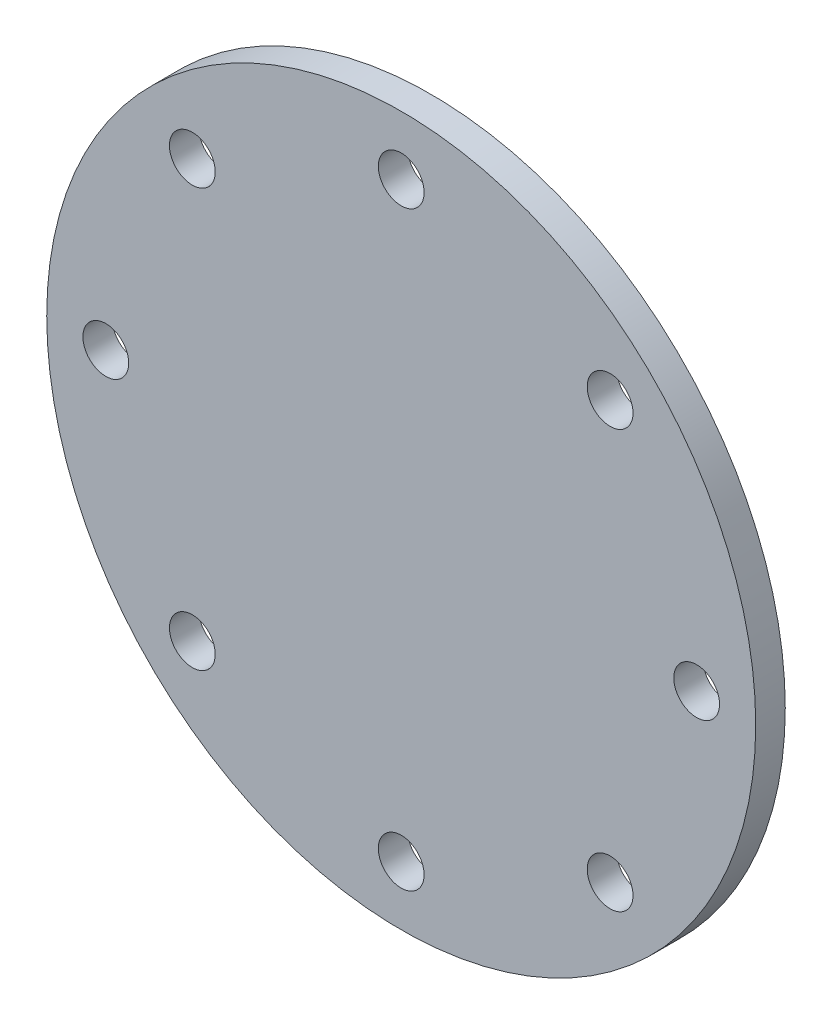
SolidWorks part; units mm, degrees
ref_plane "Front Plane" through (0, 0, 0) normal (0, 0, 1) x (1, 0, 0)
ref_plane "Top Plane" through (0, 0, 0) normal (0, 1, 0) x (1, 0, 0)
ref_plane "Right Plane" through (0, 0, 0) normal (1, 0, 0) x (0, 0, -1)
sketch "Sketch1" plane through (0, 0, 0) normal (0, 0, 1) x (1, 0, 0)
  circle A0 centre (0, 0) radius 20 construction
  circle A1 centre (0, 20) radius 1.55
  circle A2 centre (14.1421, 14.1421) radius 1.55
  circle A3 centre (20, 0) radius 1.55
  circle A4 centre (14.1421, -14.1421) radius 1.55
  circle A5 centre (0, -20) radius 1.55
  circle A6 centre (-14.1421, -14.1421) radius 1.55
  circle A7 centre (-20, 0) radius 1.55
  circle A8 centre (-14.1421, 14.1421) radius 1.55
  circle A9 centre (0, 0) radius 24
  point P22 (0, 0)
  dimension "D1" = 8
extrude "Boss-Extrude1" add sketch "Sketch1" along normal blind 2
